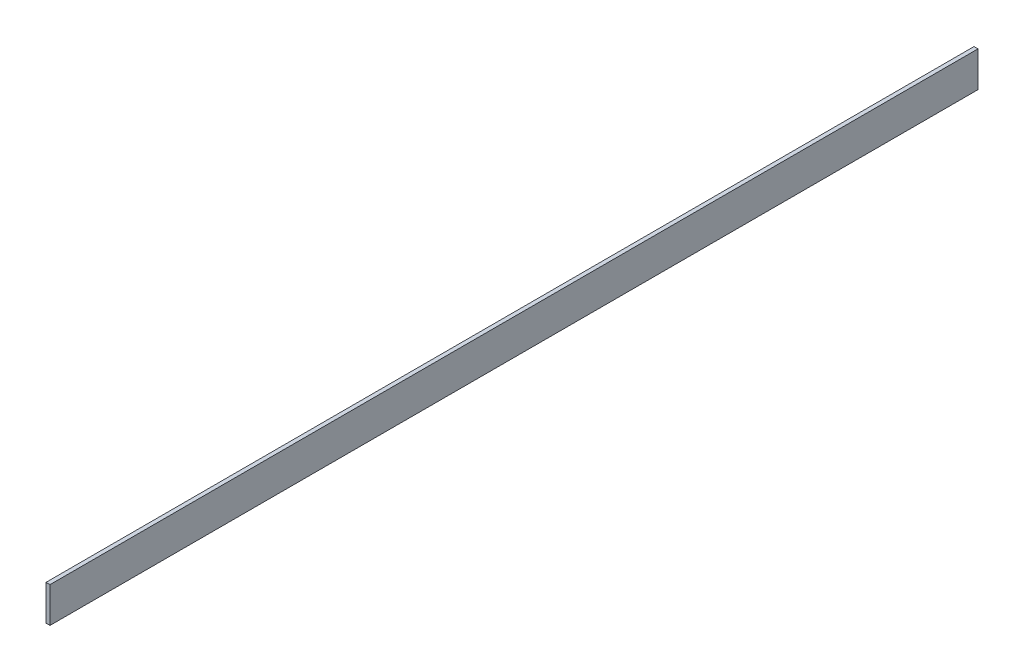
SolidWorks part; units mm, degrees
material "EPICHLOROHYDRIN"
ref_plane "前视基准面" through (0, 0, 0) normal (0, 0, 1) x (1, 0, 0)
ref_plane "上视基准面" through (0, 0, 0) normal (0, 1, 0) x (1, 0, 0)
ref_plane "右视基准面" through (0, 0, 0) normal (1, 0, 0) x (0, 0, -1)
sketch "草图1" plane through (0, 0, 0) normal (0, 1, 0) x (1, 0, 0)
  line L1 (-0.9, 210) -> (0.9, 210)
  line L2 (-0.9, 210) -> (-0.9, -210)
  line L3 (-0.9, -210) -> (0.9, -210)
  line L4 (0.9, 210) -> (0.9, -210)
  line L5 (-0.9, 210) -> (0.9, -210) construction
  line L6 (-0.9, -210) -> (0.9, 210) construction
  point P0 (0, 0)
  dimension "D1" = 1.8
  dimension "D2" = 420
extrude "凸台-拉伸1" add sketch "草图1" along normal mid plane 16 contours L2 L3 L4 L1
